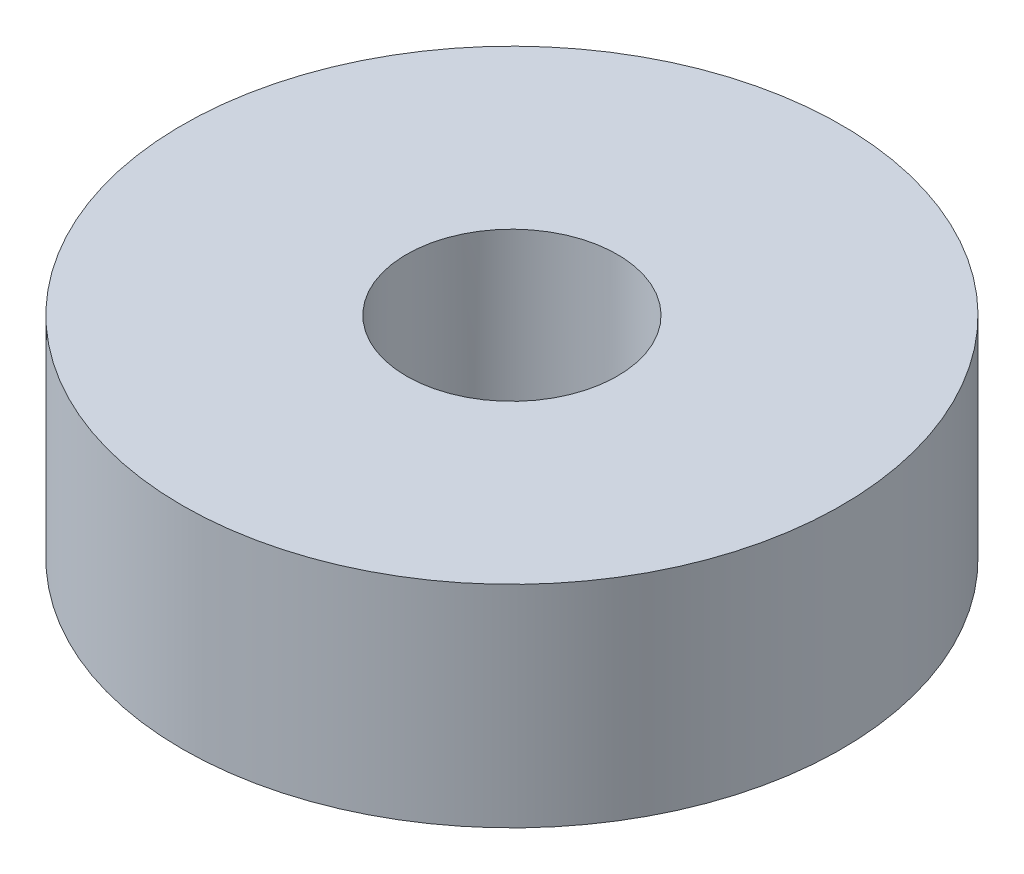
SolidWorks part; units mm, degrees
ref_plane "Front Plane" through (0, 0, 0) normal (0, 0, 1) x (1, 0, 0)
ref_plane "Top Plane" through (0, 0, 0) normal (0, 1, 0) x (1, 0, 0)
ref_plane "Right Plane" through (0, 0, 0) normal (1, 0, 0) x (0, 0, -1)
other "Graphic1"
other "Graphic (Closed) -1"
sketch "Sketch1" plane through (0, 0, 0) normal (0, 1, 0) x (1, 0, 0)
  circle A0 centre (0, 0) radius 12.5
  circle A1 centre (0, 0) radius 4
extrude "Boss-Extrude1" add sketch "Sketch1" along normal blind 6 and the other way blind 2
sketch "Sketch2" plane through (0, -2, 0) normal (0, -1, 0) x (1, 0, 0)
  line L1 (9.8583, 0) -> (4.9291, 8.5375)
  line L2 (4.9291, 8.5375) -> (-4.9291, 8.5375)
  line L3 (-4.9291, 8.5375) -> (-9.8583, 0)
  line L4 (-9.8583, 0) -> (-4.9291, -8.5375)
  line L5 (-4.9291, -8.5375) -> (4.9291, -8.5375)
  line L6 (4.9291, -8.5375) -> (9.8583, 0)
  circle A0 centre (0, 0) radius 8.5375 construction
extrude "Cut-Extrude1" cut sketch "Sketch2" against normal blind 2
